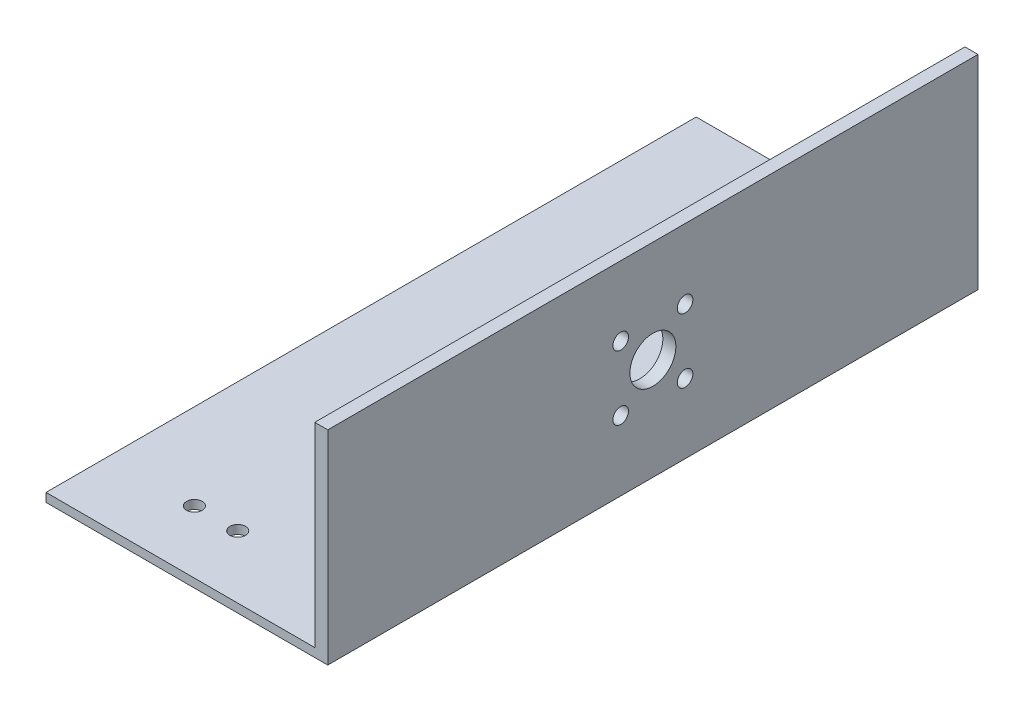
SolidWorks part; units mm, degrees
ref_plane "Alzado" through (0, 0, 0) normal (0, 0, 1) x (1, 0, 0)
ref_plane "Planta" through (0, 0, 0) normal (0, 1, 0) x (1, 0, 0)
ref_plane "Vista lateral" through (0, 0, 0) normal (1, 0, 0) x (0, 0, -1)
sketch "Croquis1" plane through (0, 0, 0) normal (0, 1, 0) x (1, 0, 0)
  line L0 (32.5, 12.25) -> (-32.5, 12.25) construction
  line L1 (32.5, 75) -> (-32.5, 75)
  line L2 (32.5, 75) -> (32.5, -75)
  line L3 (32.5, -75) -> (-32.5, -75)
  line L4 (-32.5, 75) -> (-32.5, -75)
  line L5 (32.5, 75) -> (-32.5, -75) construction
  line L6 (32.5, -75) -> (-32.5, 75) construction
  line L7 (32.5, 0) -> (-32.5, 0) construction
  line L8 (32.5, 60.57) -> (-32.5, 60.57) construction
  line L9 (-2.7, 12.25) -> (-2.7, 60.57) construction
  line L10 (-12.7, 12.25) -> (-12.7, 60.57) construction
  circle A0 centre (-2.7, 12.25) radius 1.8
  circle A1 centre (-2.7, 60.57) radius 1.8
  circle A2 centre (-12.7, -60.57) radius 1.8
  circle A3 centre (-2.7, -60.57) radius 1.8
  circle A4 centre (-12.7, 12.25) radius 1.8
  circle A5 centre (-12.7, 60.57) radius 1.8
  circle A6 centre (-12.7, -12.25) radius 1.8
  circle A7 centre (-2.7, -12.25) radius 1.8
  point P0 (0, 0)
  point P1 (0, 0)
  dimension "D3" = 10
  dimension "D4" = 3.6
  dimension "D5" = 19.8
  dimension "D1" = 150
  dimension "D2" = 65
  dimension "D6" = 48.32
  dimension "D8" = 12.25
extrude "Saliente-Extruir1" add sketch "Croquis1" along normal blind 2
sketch "Croquis2" plane through (0, 2, 0) normal (0, 1, 0) x (1, 0, 0)
  line L1 (32.5, 75) -> (29.5, 75)
  line L2 (32.5, 75) -> (32.5, -75)
  line L3 (32.5, -75) -> (29.5, -75)
  line L4 (29.5, 75) -> (29.5, -75)
  dimension "D1" = 3
extrude "Saliente-Extruir2" add sketch "Croquis2" along normal blind 45
sketch "Croquis3" plane through (32.5, 0, 0) normal (1, 0, 0) x (0, 0, -1)
  line L0 (0, 0) -> (0, 47) construction
  line L1 (-75, 0) -> (75, 0) construction
  line L2 (-75, 47) -> (75, 47) construction
  line L3 (75, 23.5) -> (-75, 23.5) construction
  line L4 (75, 47) -> (75, 0) construction
  line L5 (-75, 47) -> (-75, 0) construction
  line L6 (0, 23.5) -> (-7.4246, 16.0754) construction
  circle A0 centre (0, 23.5) radius 5.3
  circle A1 centre (0, 23.5) radius 10.5 construction
  circle A2 centre (-7.4246, 16.0754) radius 1.8
  circle A3 centre (-7.4246, 30.9246) radius 1.8
  circle A4 centre (7.4246, 30.9246) radius 1.8
  circle A5 centre (7.4246, 16.0754) radius 1.8
  point P26 (0, 23.5)
  dimension "D1" = 10.6
  dimension "D2" = 21
  dimension "D3" = 3.6
  dimension "D4" = 45
  dimension "D5" = 4
extrude "Cortar-Extruir1" cut sketch "Croquis3" against normal blind 10
